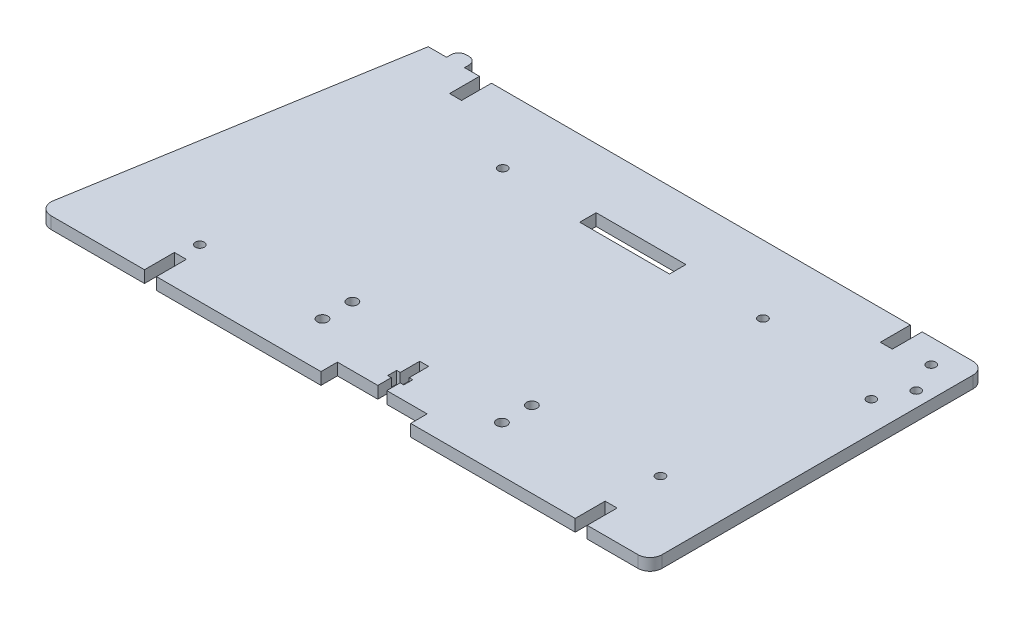
SolidWorks part; units mm, degrees
ref_plane "Front Plane" through (0, 0, 0) normal (0, 0, 1) x (1, 0, 0)
ref_plane "Top Plane" through (0, 0, 0) normal (0, 1, 0) x (1, 0, 0)
ref_plane "Right Plane" through (0, 0, 0) normal (1, 0, 0) x (0, 0, -1)
sketch "Sketch1" plane through (0, 0, 0) normal (0, 1, 0) x (1, 0, 0)
  line L0 (158.5, 0) -> (180, 0)
  line L1 (0, 0) -> (36, 0)
  line L2 (40, 112) -> (180, 112)
  line L3 (18.8632, 112) -> (25, 112)
  line L4 (205, 0) -> (205, 112)
  line L5 (184, 0) -> (205, 0)
  line L6 (95, 0) -> (95, 5.5)
  line L7 (95, 5.5) -> (108.5, 5.5)
  line L8 (125, 0) -> (125, 5.5)
  line L9 (40, 0) -> (95, 0)
  line L10 (111.5, 5.5) -> (125, 5.5)
  line L11 (31, 112) -> (36, 112)
  line L12 (108.5, 5.5) -> (108.5, 10)
  line L13 (108.5, 19.5) -> (111.5, 19.5)
  line L14 (111.5, 5.5) -> (111.5, 10)
  line L15 (107.3, 13) -> (108.5, 13)
  line L16 (107.3, 13) -> (107.3, 10)
  line L17 (107.3, 10) -> (108.5, 10)
  line L18 (112.7, 13) -> (112.7, 10)
  line L19 (111.5, 10) -> (112.7, 10)
  line L20 (111.5, 13) -> (112.7, 13)
  line L21 (125, 0) -> (155.5, 0)
  line L22 (18.8632, 112) -> (0, 0)
  line L23 (180, 0) -> (180, 10)
  line L24 (180, 10) -> (184, 10)
  line L25 (184, 0) -> (184, 10)
  line L26 (184, 112) -> (205, 112)
  line L27 (40, 0) -> (40, 10)
  line L28 (40, 10) -> (36, 10)
  line L29 (36, 0) -> (36, 10)
  line L30 (155.5, 0) -> (158.5, 0)
  line L31 (36, 112) -> (36, 102)
  line L32 (36, 102) -> (40, 102)
  line L33 (40, 112) -> (40, 102)
  line L34 (108.5, 13) -> (108.5, 19.5)
  line L35 (180, 112) -> (180, 102)
  line L36 (180, 102) -> (184, 102)
  line L37 (184, 112) -> (184, 102)
  line L38 (95, 92) -> (125, 92)
  line L39 (95, 92) -> (95, 86.5)
  line L40 (95, 86.5) -> (125, 86.5)
  line L41 (125, 92) -> (125, 86.5)
  line L42 (111.5, 13) -> (111.5, 19.5)
  line L44 (31, 112) -> (31, 116)
  line L45 (31, 116) -> (25, 116)
  line L46 (25, 112) -> (25, 116)
  circle A0 centre (153.5, 89.25) radius 1.5
  circle A1 centre (66.5, 89.25) radius 1.5
  circle A2 centre (195, 104) radius 1.5
  circle A3 centre (195, 84) radius 1.5
  circle A4 centre (200, 94) radius 1.5
  circle A5 centre (80, 15.5) radius 1.75
  circle A6 centre (80, 25.5) radius 1.75
  circle A7 centre (140, 15.5) radius 1.75
  circle A8 centre (140, 25.5) radius 1.75
  circle A9 centre (182, 26.5) radius 1.5
  circle A10 centre (38, 16.5) radius 1.5
  dimension "D38" = 3
  dimension "D39" = 3
  dimension "D40" = 3
  dimension "D48" = 3.5
  dimension "D49" = 3.5
  dimension "D52" = 3.5
  dimension "D53" = 3.5
  dimension "D56" = 3
  dimension "D57" = 3
  dimension "D60" = 3
  dimension "D61" = 3
  dimension "D1" = 112
  dimension "D3" = 30
  dimension "D4" = 5.5
  dimension "D5" = 80
  dimension "D6" = 13.5
  dimension "D7" = 3
  dimension "D8" = 4.5
  dimension "D9" = 3
  dimension "D10" = 1.2
  dimension "D11" = 5.4
  dimension "D12" = 14
  dimension "D13" = 55
  dimension "D14" = 4
  dimension "D15" = 10
  dimension "D16" = 4
  dimension "D17" = 55
  dimension "D18" = 10
  dimension "D19" = 4
  dimension "D20" = 10
  dimension "D21" = 55
  dimension "D22" = 17.1368
  dimension "D23" = 30
  dimension "D24" = 5.5
  dimension "D25" = 81
  dimension "D26" = 80
  dimension "D27" = 28.5
  dimension "D28" = 28.5
  dimension "D29" = 2.75
  dimension "D30" = 2.75
  dimension "D31" = 205
  dimension "D32" = 10
  dimension "D33" = 10
  dimension "D34" = 8
  dimension "D35" = 20
  dimension "D36" = 18
  dimension "D37" = 5
  dimension "D41" = 5
  dimension "D42" = 4
  dimension "D43" = 6
  dimension "D44" = 15
  dimension "D45" = 15
  dimension "D46" = 10
  dimension "D47" = 10
  dimension "D50" = 15
  dimension "D51" = 15
  dimension "D54" = 10
  dimension "D55" = 10
  dimension "D58" = 2
  dimension "D59" = 16.5
  dimension "D62" = 2
  dimension "D63" = 6.5
extrude "Boss-Extrude1" add sketch "Sketch1" along normal blind 4
fillet "Fillet1" radius 4 1 edges at (0, 2, 0)
fillet "Fillet2" radius 4 1 edges at (205, 2, -112)
fillet "Fillet3" radius 4 1 edges at (205, 2, 0)
fillet "Fillet4" radius 2.5 2 edges at (31, 2, -116) (25, 2, -116)
